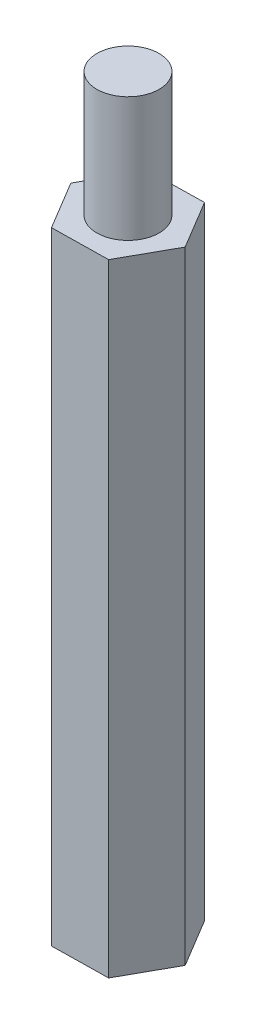
SolidWorks part; units mm, degrees
material "黄铜"
ref_plane "前视基准面" through (0, 0, 0) normal (0, 0, 1) x (1, 0, 0)
ref_plane "上视基准面" through (0, 0, 0) normal (0, 1, 0) x (1, 0, 0)
ref_plane "右视基准面" through (0, 0, 0) normal (1, 0, 0) x (0, 0, -1)
sketch "草图1" plane through (0, 0, 0) normal (0, 1, 0) x (1, 0, 0)
  line L0 (-5.8996, -0.071) -> (5.5773, 0.1142) construction
  line L1 (1.3945, -2.3278) -> (2.7132, 0.0438)
  line L2 (2.7132, 0.0438) -> (1.3187, 2.3716)
  line L3 (1.3187, 2.3716) -> (-1.3945, 2.3278)
  line L4 (-1.3945, 2.3278) -> (-2.7132, -0.0438)
  line L5 (-2.7132, -0.0438) -> (-1.3187, -2.3716)
  line L6 (-1.3187, -2.3716) -> (1.3945, -2.3278)
  circle A0 centre (0, 0) radius 2.35 construction
  circle A1 centre (0, 0) radius 1.5
  dimension "D3" = 3
  dimension "D1" = 4.7
  dimension "D2" = 60
extrude "凸台-拉伸1" add sketch "草图1" along normal blind 30
sketch "草图2" plane through (0, 30, 0) normal (0, 1, 0) x (1, 0, 0)
  circle A0 centre (0, 0) radius 1.5
  dimension "D1" = 3
extrude "凸台-拉伸2" add sketch "草图2" along normal blind 6 separate body
